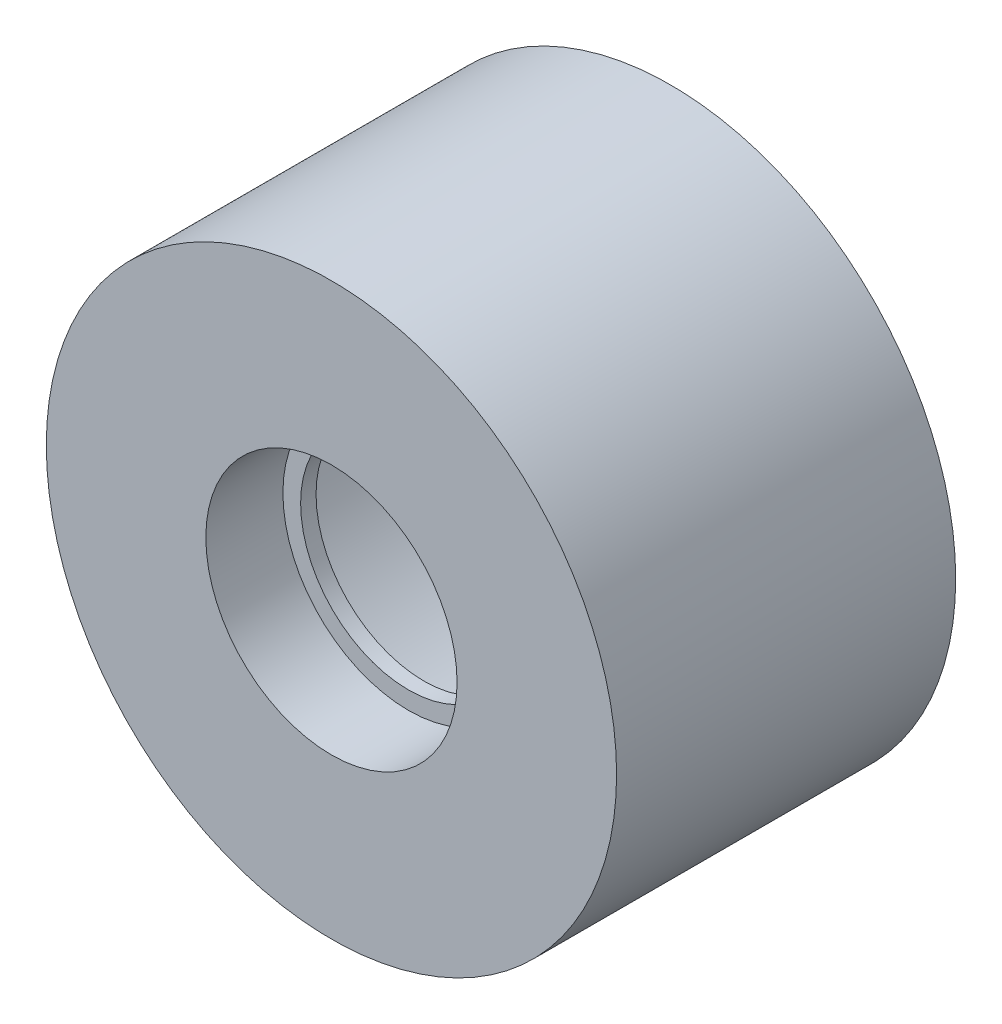
SolidWorks part; units mm, degrees
ref_plane "Alzado" through (0, 0, 0) normal (0, 0, 1) x (1, 0, 0)
ref_plane "Planta" through (0, 0, 0) normal (0, 1, 0) x (1, 0, 0)
ref_plane "Vista lateral" through (0, 0, 0) normal (1, 0, 0) x (0, 0, -1)
sketch "Croquis1" plane through (0, 0, 0) normal (0, 0, 1) x (1, 0, 0)
  circle A0 centre (0, 0) radius 16.15
  circle A1 centre (0, 0) radius 18.5
  dimension "D1" = 32.3
  dimension "D2" = 37
extrude "Saliente-Extruir1" add sketch "Croquis1" along normal blind 22
sketch "Croquis2" plane through (0, 0, 22) normal (0, 0, 1) x (1, 0, 0)
  circle A0 centre (0, 0) radius 8.15
  circle A1 centre (0, 0) radius 16.15
  dimension "D1" = 16.3
extrude "Saliente-Extruir2" add sketch "Croquis2" against normal blind 5
sketch "Croquis3" plane through (0, 0, 17) normal (0, 0, -1) x (-1, 0, 0)
  circle A0 centre (0, 0) radius 7
  circle A1 centre (0, 0) radius 16.15
  dimension "D1" = 14
extrude "Saliente-Extruir3" add sketch "Croquis3" along normal blind 1
